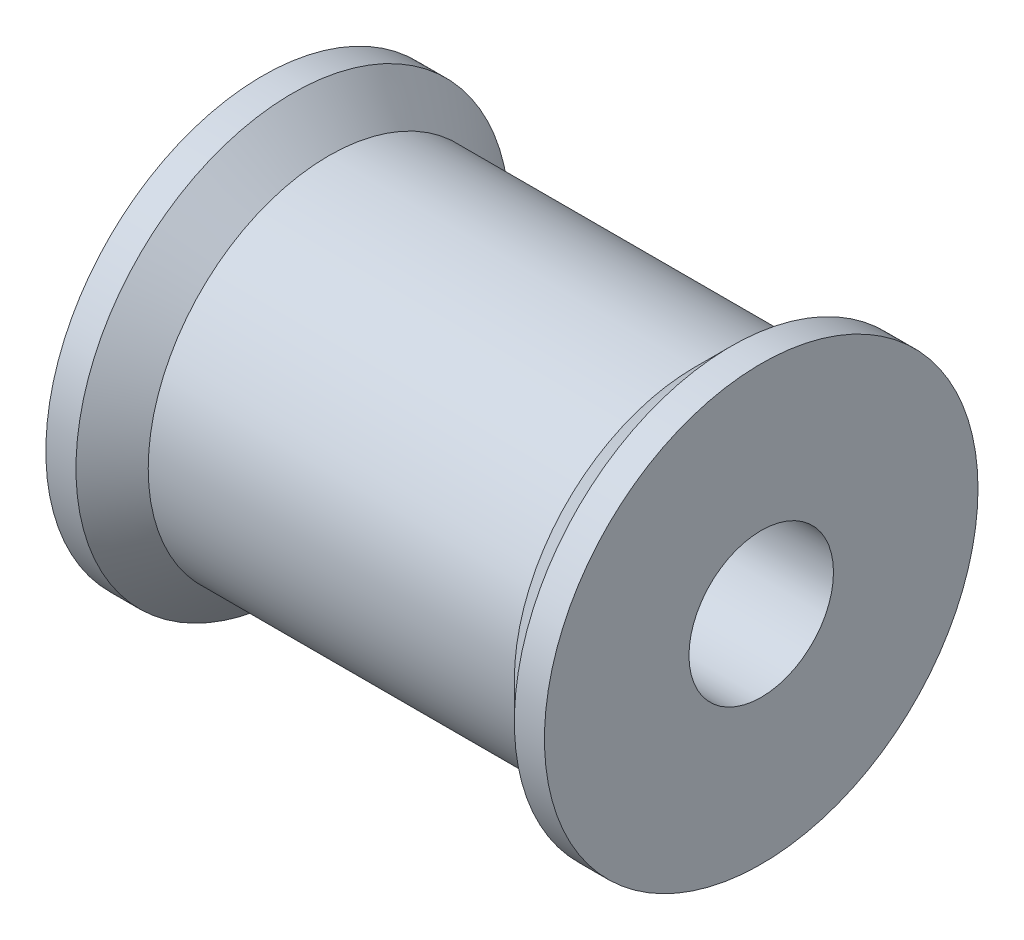
SolidWorks part; units mm, degrees
ref_plane "Front Plane" through (0, 0, 0) normal (0, 0, 1) x (1, 0, 0)
ref_plane "Top Plane" through (0, 0, 0) normal (0, 1, 0) x (1, 0, 0)
ref_plane "Right Plane" through (0, 0, 0) normal (1, 0, 0) x (0, 0, -1)
sketch "Sketch2" plane through (0, 0, 0) normal (0, 1, 0) x (1, 0, 0)
  line L0 (-10.35, 9) -> (-9.1, 9)
  line L1 (-9.1, 9) -> (-7.6, 7.5)
  line L2 (-7.6, 7.5) -> (7.6, 7.5)
  line L3 (7.6, 7.5) -> (9.1, 9)
  line L4 (9.1, 9) -> (10.35, 9)
  line L5 (10.35, 9) -> (10.35, 0)
  line L6 (-10.35, 9) -> (-10.35, 0)
  line L7 (-54.6936, 0) -> (47.2254, 0) construction
  line L8 (0, -23.2469) -> (0, 34.557) construction
  line L9 (10.35, 0) -> (-10.35, 0)
  point P13 (-7.65, 18.15)
  point P14 (0, 0)
  point P15 (0, 0)
  point P16 (0, 7.5)
  point P17 (0, 0)
  point P18 (8.9874, 8)
  point P19 (-7.6, 6.3688)
  dimension "D1" = 9
  dimension "D2" = 2.75
  dimension "D3" = 15.2
  dimension "D4" = 1.5
revolve "Revolve1" add sketch "Sketch2" angle 360 about L9
sketch "Sketch3" plane through (-10.35, 0, 0) normal (-1, 0, 0) x (0, 0, 1)
  circle A0 centre (0, 0) radius 3
  dimension "D1" = 6
extrude "Cut-Extrude1" cut sketch "Sketch3" against normal up to surface (20.7 mm away) up to face at (10.35, 0, -9)
